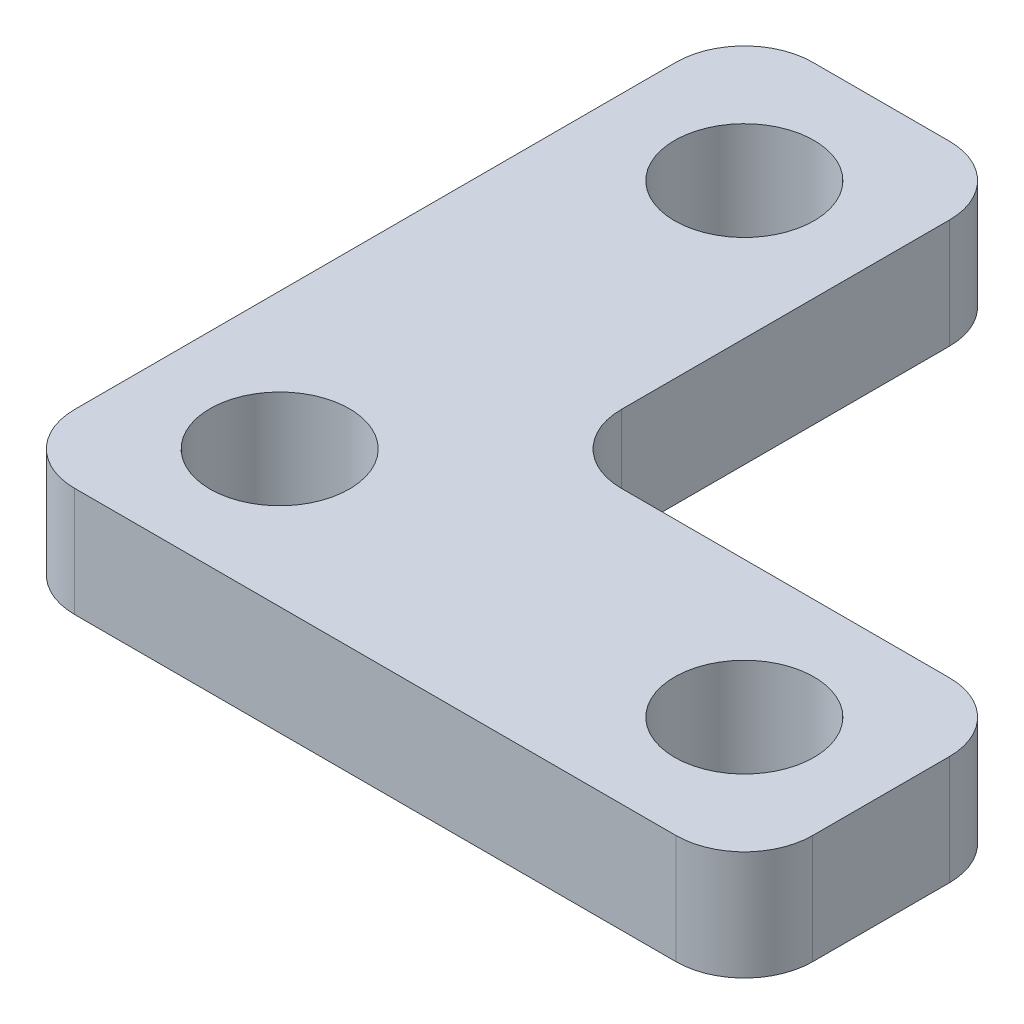
SolidWorks part; units mm, degrees
ref_plane "Front Plane" through (0, 0, 0) normal (0, 0, 1) x (1, 0, 0)
ref_plane "Top Plane" through (0, 0, 0) normal (0, 1, 0) x (1, 0, 0)
ref_plane "Right Plane" through (0, 0, 0) normal (1, 0, 0) x (0, 0, -1)
sketch "Sketch1" plane through (0, 0, 0) normal (0, 1, 0) x (1, 0, 0)
  line L0 (0, 2.5) -> (0, 24.5)
  line L1 (2.5, 27) -> (7.5, 27)
  line L2 (10, 24.5) -> (10, 12.5)
  line L3 (12.5, 10) -> (24.5, 10)
  line L4 (27, 7.5) -> (27, 2.5)
  line L5 (24.5, 0) -> (2.5, 0)
  circle A0 centre (22, 5) radius 2.55
  circle A1 centre (5, 5) radius 2.55
  circle A2 centre (5, 22) radius 2.55
  arc A3 (10, 12.5) -> (12.5, 10) centre (12.5, 12.5) ccw
  arc A4 (7.5, 27) -> (10, 24.5) centre (7.5, 24.5) cw
  arc A5 (0, 24.5) -> (2.5, 27) centre (2.5, 24.5) cw
  arc A6 (0, 2.5) -> (2.5, 0) centre (2.5, 2.5) ccw
  arc A7 (24.5, 0) -> (27, 2.5) centre (24.5, 2.5) ccw
  arc A8 (27, 7.5) -> (24.5, 10) centre (24.5, 7.5) ccw
  point P25 (0, 0)
  dimension "D1" = 5.1
  dimension "D10" = 2.5
  dimension "D2" = 17
  dimension "D3" = 17
  dimension "D4" = 5
  dimension "D5" = 5
  dimension "D6" = 5
  dimension "D7" = 5
  dimension "D8" = 5
  dimension "D9" = 5
extrude "Boss-Extrude1" add sketch "Sketch1" along normal blind 4
